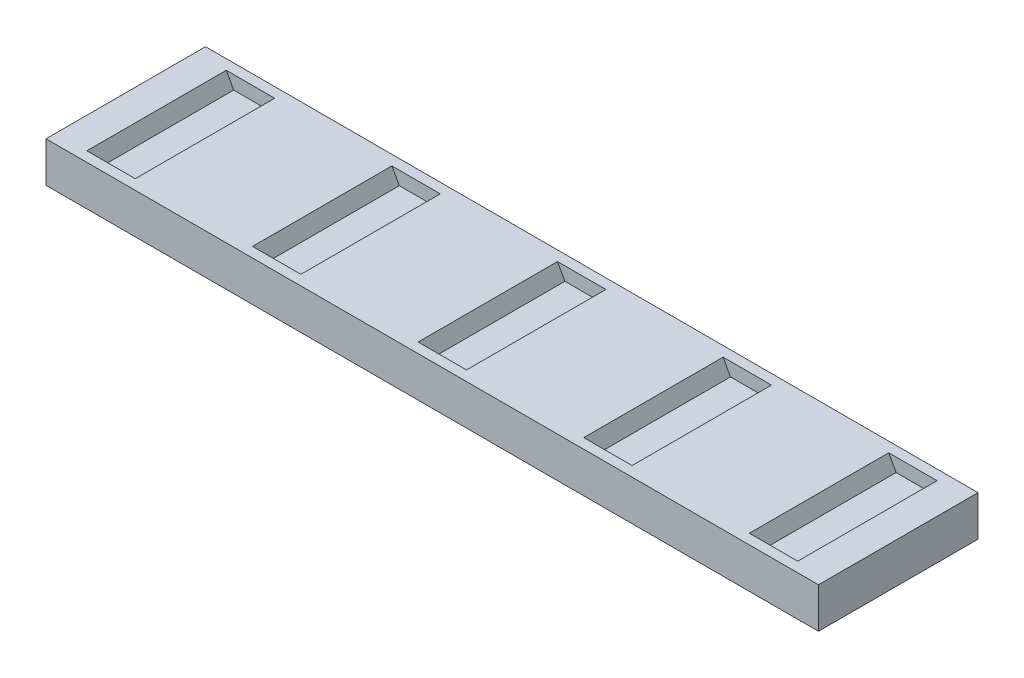
SolidWorks part; units mm, degrees
material "ABS"
ref_plane "Front Plane" through (0, 0, 0) normal (0, 0, 1) x (1, 0, 0)
ref_plane "Top Plane" through (0, 0, 0) normal (0, 1, 0) x (1, 0, 0)
ref_plane "Right Plane" through (0, 0, 0) normal (1, 0, 0) x (0, 0, -1)
sketch "ｽｹｯﾁ1" plane through (0, 0, 0) normal (0, 0, 1) x (1, 0, 0)
  line L0 (0, 0) -> (167.7493, 0) construction
  line B0 (0, 6.1517) -> (0, -7.9464) construction
  line B1 (-3.1032, 0) -> (3.1032, 0)
  line B2 (3.1032, 0) -> (2.3481, -2.0746)
  line B3 (1.0607, -2.976) -> (-1.0607, -2.976)
  line B4 (-2.3481, -2.0746) -> (-3.1032, 0)
  arc B5 (2.3481, -2.0746) -> (1.0607, -2.976) centre (1.0607, -1.606) cw
  arc B6 (-1.0607, -2.976) -> (-2.3481, -2.0746) centre (-1.0607, -1.606) cw
sketch_block_instance "ﾌﾞﾛｯｸ1-1"
sketch_block "ﾌﾞﾛｯｸ1" parameters "D2"=1.37, "D1"=40
sketch "ｽｹｯﾁ3" plane through (0, 0, 0) normal (0, 0, 1) x (1, 0, 0)
  line L0 (0, 6.1517) -> (0, -7.9464) construction
  line L1 (-2.3481, -2.0746) -> (-3.1032, 0) construction
  line L2 (1.0607, -2.976) -> (-1.0607, -2.976) construction
  line L3 (3.1032, 0) -> (2.3481, -2.0746) construction
  line L4 (3.1032, 0) -> (9.5968, 0)
  line L5 (0, 0) -> (167.7493, 0) construction
  line L6 (10.3519, -2.0746) -> (9.5968, 0)
  line L7 (13.7607, -2.976) -> (11.6393, -2.976)
  line L8 (0, 6.1517) -> (0, -7.9464) construction
  line L9 (-2.3481, -2.0746) -> (-3.1032, 0)
  line L10 (1.0607, -2.976) -> (-1.0607, -2.976)
  line L11 (3.1032, 0) -> (2.3481, -2.0746)
  line L12 (15.8032, 0) -> (15.0481, -2.0746)
  line L13 (12.7, 6.1517) -> (12.7, -7.9464) construction
  line L14 (15.8032, 0) -> (22.2968, 0)
  line L15 (23.0519, -2.0746) -> (22.2968, 0)
  line L16 (26.4607, -2.976) -> (24.3393, -2.976)
  line L17 (28.5032, 0) -> (27.7481, -2.0746)
  line L18 (25.4, 6.1517) -> (25.4, -7.9464) construction
  line L19 (28.5032, 0) -> (34.9968, 0)
  line L20 (35.7519, -2.0746) -> (34.9968, 0)
  line L21 (39.1607, -2.976) -> (37.0393, -2.976)
  line L22 (41.2032, 0) -> (40.4481, -2.0746)
  line L23 (38.1, 6.1517) -> (38.1, -7.9464) construction
  line L24 (41.2032, 0) -> (47.6968, 0)
  line L25 (48.4519, -2.0746) -> (47.6968, 0)
  line L26 (51.8607, -2.976) -> (49.7393, -2.976)
  line L27 (53.9032, 0) -> (53.1481, -2.0746)
  line L28 (50.8, 6.1517) -> (50.8, -7.9464) construction
  line L29 (53.9032, 0) -> (60.3968, 0)
  line L30 (61.1519, -2.0746) -> (60.3968, 0)
  line L31 (64.5607, -2.976) -> (62.4393, -2.976)
  line L32 (66.6032, 0) -> (65.8481, -2.0746)
  line L33 (63.5, 6.1517) -> (63.5, -7.9464) construction
  line L34 (66.6032, 0) -> (73.0968, 0)
  line L35 (73.8519, -2.0746) -> (73.0968, 0)
  line L36 (77.2607, -2.976) -> (75.1393, -2.976)
  line L37 (79.3032, 0) -> (78.5481, -2.0746)
  line L38 (76.2, 6.1517) -> (76.2, -7.9464) construction
  line L39 (79.3032, 0) -> (85.7968, 0)
  line L40 (86.5519, -2.0746) -> (85.7968, 0)
  line L41 (89.9607, -2.976) -> (87.8393, -2.976)
  line L42 (92.0032, 0) -> (91.2481, -2.0746)
  line L43 (88.9, 6.1517) -> (88.9, -7.9464) construction
  line L44 (92.0032, 0) -> (98.4968, 0)
  line L45 (99.2519, -2.0746) -> (98.4968, 0)
  line L46 (102.6607, -2.976) -> (100.5393, -2.976)
  line L47 (104.7032, 0) -> (103.9481, -2.0746)
  line L48 (101.6, 6.1517) -> (101.6, -7.9464) construction
  line L49 (104.7032, 0) -> (111.1968, 0)
  line L50 (111.9519, -2.0746) -> (111.1968, 0)
  line L51 (115.3607, -2.976) -> (113.2393, -2.976)
  line L52 (117.4032, 0) -> (116.6481, -2.0746)
  line L53 (114.3, 6.1517) -> (114.3, -7.9464) construction
  line L54 (117.4032, 0) -> (123.8968, 0)
  line L55 (124.6519, -2.0746) -> (123.8968, 0)
  line L56 (128.0607, -2.976) -> (125.9393, -2.976)
  line L57 (130.1032, 0) -> (129.3481, -2.0746)
  line L58 (127, 6.1517) -> (127, -7.9464) construction
  line L59 (130.1032, 0) -> (136.5968, 0)
  line L60 (137.3519, -2.0746) -> (136.5968, 0)
  line L61 (140.7607, -2.976) -> (138.6393, -2.976)
  line L62 (142.8032, 0) -> (142.0481, -2.0746)
  line L63 (139.7, 6.1517) -> (139.7, -7.9464) construction
  line L64 (142.8032, 0) -> (149.2968, 0)
  line L65 (150.0519, -2.0746) -> (149.2968, 0)
  line L66 (153.4607, -2.976) -> (151.3393, -2.976)
  line L67 (155.5032, 0) -> (154.7481, -2.0746)
  line L68 (152.4, 6.1517) -> (152.4, -7.9464) construction
  line L69 (155.5032, 0) -> (161.9968, 0)
  line L70 (162.7519, -2.0746) -> (161.9968, 0)
  line L71 (166.1607, -2.976) -> (164.0393, -2.976)
  line L72 (168.2032, 0) -> (167.4481, -2.0746)
  line L73 (165.1, 6.1517) -> (165.1, -7.9464) construction
  line L74 (168.2032, 0) -> (174.6968, 0)
  line L75 (175.4519, -2.0746) -> (174.6968, 0)
  line L76 (178.8607, -2.976) -> (176.7393, -2.976)
  line L77 (180.9032, 0) -> (180.1481, -2.0746)
  line L78 (177.8, 6.1517) -> (177.8, -7.9464) construction
  line L79 (180.9032, 0) -> (187.3968, 0)
  line L80 (188.1519, -2.0746) -> (187.3968, 0)
  line L81 (191.5607, -2.976) -> (189.4393, -2.976)
  line L82 (193.6032, 0) -> (192.8481, -2.0746)
  line L83 (190.5, 6.1517) -> (190.5, -7.9464) construction
  line L84 (193.6032, 0) -> (200.0968, 0)
  line L85 (200.8519, -2.0746) -> (200.0968, 0)
  line L86 (204.2607, -2.976) -> (202.1393, -2.976)
  line L87 (206.3032, 0) -> (205.5481, -2.0746)
  line L88 (203.2, 6.1517) -> (203.2, -7.9464) construction
  line L89 (206.3032, 0) -> (212.7968, 0)
  line L90 (213.5519, -2.0746) -> (212.7968, 0)
  line L91 (216.9607, -2.976) -> (214.8393, -2.976)
  line L92 (219.0032, 0) -> (218.2481, -2.0746)
  line L93 (215.9, 6.1517) -> (215.9, -7.9464) construction
  line L94 (219.0032, 0) -> (225.4968, 0)
  line L95 (226.2519, -2.0746) -> (225.4968, 0)
  line L96 (229.6607, -2.976) -> (227.5393, -2.976)
  line L97 (231.7032, 0) -> (230.9481, -2.0746)
  line L98 (228.6, 6.1517) -> (228.6, -7.9464) construction
  line L99 (231.7032, 0) -> (238.1968, 0)
  arc A0 (-2.3481, -2.0746) -> (-1.0607, -2.976) centre (-1.0607, -1.606) ccw construction
  arc A1 (1.0607, -2.976) -> (2.3481, -2.0746) centre (1.0607, -1.606) ccw construction
  arc A2 (10.3519, -2.0746) -> (11.6393, -2.976) centre (11.6393, -1.606) ccw
  arc A3 (13.7607, -2.976) -> (15.0481, -2.0746) centre (13.7607, -1.606) ccw
  arc A4 (-2.3481, -2.0746) -> (-1.0607, -2.976) centre (-1.0607, -1.606) ccw
  arc A5 (1.0607, -2.976) -> (2.3481, -2.0746) centre (1.0607, -1.606) ccw
  arc A6 (23.0519, -2.0746) -> (24.3393, -2.976) centre (24.3393, -1.606) ccw
  arc A7 (26.4607, -2.976) -> (27.7481, -2.0746) centre (26.4607, -1.606) ccw
  arc A8 (35.7519, -2.0746) -> (37.0393, -2.976) centre (37.0393, -1.606) ccw
  arc A9 (39.1607, -2.976) -> (40.4481, -2.0746) centre (39.1607, -1.606) ccw
  arc A10 (48.4519, -2.0746) -> (49.7393, -2.976) centre (49.7393, -1.606) ccw
  arc A11 (51.8607, -2.976) -> (53.1481, -2.0746) centre (51.8607, -1.606) ccw
  arc A12 (61.1519, -2.0746) -> (62.4393, -2.976) centre (62.4393, -1.606) ccw
  arc A13 (64.5607, -2.976) -> (65.8481, -2.0746) centre (64.5607, -1.606) ccw
  arc A14 (73.8519, -2.0746) -> (75.1393, -2.976) centre (75.1393, -1.606) ccw
  arc A15 (77.2607, -2.976) -> (78.5481, -2.0746) centre (77.2607, -1.606) ccw
  arc A16 (86.5519, -2.0746) -> (87.8393, -2.976) centre (87.8393, -1.606) ccw
  arc A17 (89.9607, -2.976) -> (91.2481, -2.0746) centre (89.9607, -1.606) ccw
  arc A18 (99.2519, -2.0746) -> (100.5393, -2.976) centre (100.5393, -1.606) ccw
  arc A19 (102.6607, -2.976) -> (103.9481, -2.0746) centre (102.6607, -1.606) ccw
  arc A20 (111.9519, -2.0746) -> (113.2393, -2.976) centre (113.2393, -1.606) ccw
  arc A21 (115.3607, -2.976) -> (116.6481, -2.0746) centre (115.3607, -1.606) ccw
  arc A22 (124.6519, -2.0746) -> (125.9393, -2.976) centre (125.9393, -1.606) ccw
  arc A23 (128.0607, -2.976) -> (129.3481, -2.0746) centre (128.0607, -1.606) ccw
  arc A24 (137.3519, -2.0746) -> (138.6393, -2.976) centre (138.6393, -1.606) ccw
  arc A25 (140.7607, -2.976) -> (142.0481, -2.0746) centre (140.7607, -1.606) ccw
  arc A26 (150.0519, -2.0746) -> (151.3393, -2.976) centre (151.3393, -1.606) ccw
  arc A27 (153.4607, -2.976) -> (154.7481, -2.0746) centre (153.4607, -1.606) ccw
  arc A28 (162.7519, -2.0746) -> (164.0393, -2.976) centre (164.0393, -1.606) ccw
  arc A29 (166.1607, -2.976) -> (167.4481, -2.0746) centre (166.1607, -1.606) ccw
  arc A30 (175.4519, -2.0746) -> (176.7393, -2.976) centre (176.7393, -1.606) ccw
  arc A31 (178.8607, -2.976) -> (180.1481, -2.0746) centre (178.8607, -1.606) ccw
  arc A32 (188.1519, -2.0746) -> (189.4393, -2.976) centre (189.4393, -1.606) ccw
  arc A33 (191.5607, -2.976) -> (192.8481, -2.0746) centre (191.5607, -1.606) ccw
  arc A34 (200.8519, -2.0746) -> (202.1393, -2.976) centre (202.1393, -1.606) ccw
  arc A35 (204.2607, -2.976) -> (205.5481, -2.0746) centre (204.2607, -1.606) ccw
  arc A36 (213.5519, -2.0746) -> (214.8393, -2.976) centre (214.8393, -1.606) ccw
  arc A37 (216.9607, -2.976) -> (218.2481, -2.0746) centre (216.9607, -1.606) ccw
  arc A38 (226.2519, -2.0746) -> (227.5393, -2.976) centre (227.5393, -1.606) ccw
  arc A39 (229.6607, -2.976) -> (230.9481, -2.0746) centre (229.6607, -1.606) ccw
  dimension "D1" = 19
  dimension "D2" = 12.7
sketch "ｽｹｯﾁ4" plane through (0, 0, 0) normal (0, 0, 1) x (1, 0, 0)
  line L0 (0, 6.1517) -> (0, -7.9464) construction
  line L1 (1.0607, -2.976) -> (-1.0607, -2.976) construction
  line L2 (3.1032, 0) -> (2.3481, -2.0746) construction
  line L3 (3.1032, 0) -> (9.5968, 0) construction
  line L4 (10.3519, -2.0746) -> (9.5968, 0) construction
  line L5 (13.7607, -2.976) -> (11.6393, -2.976) construction
  line L6 (15.8032, 0) -> (15.0481, -2.0746) construction
  line L7 (15.8032, 0) -> (22.2968, 0) construction
  line L8 (23.0519, -2.0746) -> (22.2968, 0) construction
  line L9 (26.4607, -2.976) -> (24.3393, -2.976) construction
  line L10 (28.5032, 0) -> (27.7481, -2.0746) construction
  line L11 (28.5032, 0) -> (34.9968, 0) construction
  line L12 (35.7519, -2.0746) -> (34.9968, 0) construction
  line L13 (39.1607, -2.976) -> (37.0393, -2.976) construction
  line L14 (41.2032, 0) -> (40.4481, -2.0746) construction
  line L15 (41.2032, 0) -> (47.6968, 0) construction
  line L16 (48.4519, -2.0746) -> (47.6968, 0) construction
  line L17 (51.8607, -2.976) -> (49.7393, -2.976) construction
  line L18 (53.9032, 0) -> (53.1481, -2.0746) construction
  line L19 (53.9032, 0) -> (60.3968, 0) construction
  line L20 (61.1519, -2.0746) -> (60.3968, 0) construction
  line L21 (64.5607, -2.976) -> (62.4393, -2.976) construction
  line L22 (66.6032, 0) -> (65.8481, -2.0746) construction
  line L23 (66.6032, 0) -> (73.0968, 0) construction
  line L24 (73.8519, -2.0746) -> (73.0968, 0) construction
  line L25 (77.2607, -2.976) -> (75.1393, -2.976) construction
  line L26 (79.3032, 0) -> (78.5481, -2.0746) construction
  line L27 (79.3032, 0) -> (85.7968, 0) construction
  line L28 (86.5519, -2.0746) -> (85.7968, 0) construction
  line L29 (89.9607, -2.976) -> (87.8393, -2.976) construction
  line L30 (92.0032, 0) -> (91.2481, -2.0746) construction
  line L31 (92.0032, 0) -> (98.4968, 0) construction
  line L32 (99.2519, -2.0746) -> (98.4968, 0) construction
  line L33 (102.6607, -2.976) -> (100.5393, -2.976) construction
  line L34 (104.7032, 0) -> (103.9481, -2.0746) construction
  line L35 (104.7032, 0) -> (111.1968, 0) construction
  line L36 (111.9519, -2.0746) -> (111.1968, 0) construction
  line L37 (115.3607, -2.976) -> (113.2393, -2.976) construction
  line L38 (117.4032, 0) -> (116.6481, -2.0746) construction
  line L39 (117.4032, 0) -> (123.8968, 0) construction
  line L40 (124.6519, -2.0746) -> (123.8968, 0) construction
  line L41 (128.0607, -2.976) -> (125.9393, -2.976) construction
  line L42 (130.1032, 0) -> (129.3481, -2.0746) construction
  line L43 (130.1032, 0) -> (136.5968, 0) construction
  line L44 (137.3519, -2.0746) -> (136.5968, 0) construction
  line L45 (140.7607, -2.976) -> (138.6393, -2.976) construction
  line L46 (142.8032, 0) -> (142.0481, -2.0746) construction
  line L47 (142.8032, 0) -> (149.2968, 0) construction
  line L48 (150.0519, -2.0746) -> (149.2968, 0) construction
  line L49 (153.4607, -2.976) -> (151.3393, -2.976) construction
  line L50 (155.5032, 0) -> (154.7481, -2.0746) construction
  line L51 (155.5032, 0) -> (161.9968, 0) construction
  line L52 (162.7519, -2.0746) -> (161.9968, 0) construction
  line L53 (166.1607, -2.976) -> (164.0393, -2.976) construction
  line L54 (168.2032, 0) -> (167.4481, -2.0746) construction
  line L55 (168.2032, 0) -> (174.6968, 0) construction
  line L56 (175.4519, -2.0746) -> (174.6968, 0) construction
  line L57 (178.8607, -2.976) -> (176.7393, -2.976) construction
  line L58 (180.9032, 0) -> (180.1481, -2.0746) construction
  line L59 (180.9032, 0) -> (187.3968, 0) construction
  line L60 (188.1519, -2.0746) -> (187.3968, 0) construction
  line L61 (191.5607, -2.976) -> (189.4393, -2.976) construction
  line L62 (193.6032, 0) -> (192.8481, -2.0746) construction
  line L63 (193.6032, 0) -> (200.0968, 0) construction
  line L64 (200.8519, -2.0746) -> (200.0968, 0) construction
  line L65 (204.2607, -2.976) -> (202.1393, -2.976) construction
  line L66 (206.3032, 0) -> (205.5481, -2.0746) construction
  line L67 (206.3032, 0) -> (212.7968, 0) construction
  line L68 (213.5519, -2.0746) -> (212.7968, 0) construction
  line L69 (216.9607, -2.976) -> (214.8393, -2.976) construction
  line L70 (219.0032, 0) -> (218.2481, -2.0746) construction
  line L71 (219.0032, 0) -> (225.4968, 0) construction
  line L72 (226.2519, -2.0746) -> (225.4968, 0) construction
  line L73 (229.6607, -2.976) -> (227.5393, -2.976) construction
  line L74 (115, 61.4098) -> (115, -57.3786) construction
  line L77 (1.0607, -2.976) -> (0, -2.976)
  line L78 (3.1032, 0) -> (2.3481, -2.0746)
  line L79 (3.1032, 0) -> (9.5968, 0)
  line L80 (10.3519, -2.0746) -> (9.5968, 0)
  line L81 (13.7607, -2.976) -> (11.6393, -2.976)
  line L82 (15.8032, 0) -> (15.0481, -2.0746)
  line L83 (15.8032, 0) -> (22.2968, 0)
  line L84 (23.0519, -2.0746) -> (22.2968, 0)
  line L85 (26.4607, -2.976) -> (24.3393, -2.976)
  line L86 (28.5032, 0) -> (27.7481, -2.0746)
  line L87 (28.5032, 0) -> (34.9968, 0)
  line L88 (35.7519, -2.0746) -> (34.9968, 0)
  line L89 (39.1607, -2.976) -> (37.0393, -2.976)
  line L90 (41.2032, 0) -> (40.4481, -2.0746)
  line L91 (41.2032, 0) -> (47.6968, 0)
  line L92 (48.4519, -2.0746) -> (47.6968, 0)
  line L93 (51.8607, -2.976) -> (49.7393, -2.976)
  line L94 (53.9032, 0) -> (53.1481, -2.0746)
  line L95 (53.9032, 0) -> (60.3968, 0)
  line L96 (61.1519, -2.0746) -> (60.3968, 0)
  line L97 (64.5607, -2.976) -> (62.4393, -2.976)
  line L98 (66.6032, 0) -> (65.8481, -2.0746)
  line L99 (66.6032, 0) -> (73.0968, 0)
  line L100 (73.8519, -2.0746) -> (73.0968, 0)
  line L101 (77.2607, -2.976) -> (75.1393, -2.976)
  line L102 (79.3032, 0) -> (78.5481, -2.0746)
  line L103 (79.3032, 0) -> (85.7968, 0)
  line L104 (86.5519, -2.0746) -> (85.7968, 0)
  line L105 (89.9607, -2.976) -> (87.8393, -2.976)
  line L106 (92.0032, 0) -> (91.2481, -2.0746)
  line L107 (92.0032, 0) -> (98.4968, 0)
  line L108 (99.2519, -2.0746) -> (98.4968, 0)
  line L109 (102.6607, -2.976) -> (100.5393, -2.976)
  line L110 (104.7032, 0) -> (103.9481, -2.0746)
  line L111 (104.7032, 0) -> (111.1968, 0)
  line L112 (111.9519, -2.0746) -> (111.1968, 0)
  line L113 (115.3607, -2.976) -> (113.2393, -2.976)
  line L114 (117.4032, 0) -> (116.6481, -2.0746)
  line L115 (117.4032, 0) -> (123.8968, 0)
  line L116 (124.6519, -2.0746) -> (123.8968, 0)
  line L117 (128.0607, -2.976) -> (125.9393, -2.976)
  line L118 (130.1032, 0) -> (129.3481, -2.0746)
  line L119 (130.1032, 0) -> (136.5968, 0)
  line L120 (137.3519, -2.0746) -> (136.5968, 0)
  line L121 (140.7607, -2.976) -> (138.6393, -2.976)
  line L122 (142.8032, 0) -> (142.0481, -2.0746)
  line L123 (142.8032, 0) -> (149.2968, 0)
  line L124 (150.0519, -2.0746) -> (149.2968, 0)
  line L125 (153.4607, -2.976) -> (151.3393, -2.976)
  line L126 (155.5032, 0) -> (154.7481, -2.0746)
  line L127 (155.5032, 0) -> (161.9968, 0)
  line L128 (162.7519, -2.0746) -> (161.9968, 0)
  line L129 (166.1607, -2.976) -> (164.0393, -2.976)
  line L130 (168.2032, 0) -> (167.4481, -2.0746)
  line L131 (168.2032, 0) -> (174.6968, 0)
  line L132 (175.4519, -2.0746) -> (174.6968, 0)
  line L133 (178.8607, -2.976) -> (176.7393, -2.976)
  line L134 (180.9032, 0) -> (180.1481, -2.0746)
  line L135 (180.9032, 0) -> (187.3968, 0)
  line L136 (188.1519, -2.0746) -> (187.3968, 0)
  line L137 (191.5607, -2.976) -> (189.4393, -2.976)
  line L138 (193.6032, 0) -> (192.8481, -2.0746)
  line L139 (193.6032, 0) -> (200.0968, 0)
  line L140 (200.8519, -2.0746) -> (200.0968, 0)
  line L141 (204.2607, -2.976) -> (202.1393, -2.976)
  line L142 (206.3032, 0) -> (205.5481, -2.0746)
  line L143 (206.3032, 0) -> (212.7968, 0)
  line L144 (213.5519, -2.0746) -> (212.7968, 0)
  line L145 (216.9607, -2.976) -> (214.8393, -2.976)
  line L146 (219.0032, 0) -> (218.2481, -2.0746)
  line L147 (219.0032, 0) -> (225.4968, 0)
  line L148 (226.2519, -2.0746) -> (225.4968, 0)
  line L149 (230, -2.976) -> (227.5393, -2.976)
  line L150 (0, -7) -> (55.8373, -7) construction
  line L152 (0, -2.976) -> (0, -15)
  line L153 (0, -15) -> (230, -15)
  line L154 (230, -2.976) -> (230, -15)
  arc A1 (1.0607, -2.976) -> (2.3481, -2.0746) centre (1.0607, -1.606) ccw construction
  arc A2 (10.3519, -2.0746) -> (11.6393, -2.976) centre (11.6393, -1.606) ccw construction
  arc A3 (13.7607, -2.976) -> (15.0481, -2.0746) centre (13.7607, -1.606) ccw construction
  arc A4 (23.0519, -2.0746) -> (24.3393, -2.976) centre (24.3393, -1.606) ccw construction
  arc A5 (26.4607, -2.976) -> (27.7481, -2.0746) centre (26.4607, -1.606) ccw construction
  arc A6 (35.7519, -2.0746) -> (37.0393, -2.976) centre (37.0393, -1.606) ccw construction
  arc A7 (39.1607, -2.976) -> (40.4481, -2.0746) centre (39.1607, -1.606) ccw construction
  arc A8 (48.4519, -2.0746) -> (49.7393, -2.976) centre (49.7393, -1.606) ccw construction
  arc A9 (51.8607, -2.976) -> (53.1481, -2.0746) centre (51.8607, -1.606) ccw construction
  arc A10 (61.1519, -2.0746) -> (62.4393, -2.976) centre (62.4393, -1.606) ccw construction
  arc A11 (64.5607, -2.976) -> (65.8481, -2.0746) centre (64.5607, -1.606) ccw construction
  arc A12 (73.8519, -2.0746) -> (75.1393, -2.976) centre (75.1393, -1.606) ccw construction
  arc A13 (77.2607, -2.976) -> (78.5481, -2.0746) centre (77.2607, -1.606) ccw construction
  arc A14 (86.5519, -2.0746) -> (87.8393, -2.976) centre (87.8393, -1.606) ccw construction
  arc A15 (89.9607, -2.976) -> (91.2481, -2.0746) centre (89.9607, -1.606) ccw construction
  arc A16 (99.2519, -2.0746) -> (100.5393, -2.976) centre (100.5393, -1.606) ccw construction
  arc A17 (102.6607, -2.976) -> (103.9481, -2.0746) centre (102.6607, -1.606) ccw construction
  arc A18 (111.9519, -2.0746) -> (113.2393, -2.976) centre (113.2393, -1.606) ccw construction
  arc A19 (115.3607, -2.976) -> (116.6481, -2.0746) centre (115.3607, -1.606) ccw construction
  arc A20 (124.6519, -2.0746) -> (125.9393, -2.976) centre (125.9393, -1.606) ccw construction
  arc A21 (128.0607, -2.976) -> (129.3481, -2.0746) centre (128.0607, -1.606) ccw construction
  arc A22 (137.3519, -2.0746) -> (138.6393, -2.976) centre (138.6393, -1.606) ccw construction
  arc A23 (140.7607, -2.976) -> (142.0481, -2.0746) centre (140.7607, -1.606) ccw construction
  arc A24 (150.0519, -2.0746) -> (151.3393, -2.976) centre (151.3393, -1.606) ccw construction
  arc A25 (153.4607, -2.976) -> (154.7481, -2.0746) centre (153.4607, -1.606) ccw construction
  arc A26 (162.7519, -2.0746) -> (164.0393, -2.976) centre (164.0393, -1.606) ccw construction
  arc A27 (166.1607, -2.976) -> (167.4481, -2.0746) centre (166.1607, -1.606) ccw construction
  arc A28 (175.4519, -2.0746) -> (176.7393, -2.976) centre (176.7393, -1.606) ccw construction
  arc A29 (178.8607, -2.976) -> (180.1481, -2.0746) centre (178.8607, -1.606) ccw construction
  arc A30 (188.1519, -2.0746) -> (189.4393, -2.976) centre (189.4393, -1.606) ccw construction
  arc A31 (191.5607, -2.976) -> (192.8481, -2.0746) centre (191.5607, -1.606) ccw construction
  arc A32 (200.8519, -2.0746) -> (202.1393, -2.976) centre (202.1393, -1.606) ccw construction
  arc A33 (204.2607, -2.976) -> (205.5481, -2.0746) centre (204.2607, -1.606) ccw construction
  arc A34 (213.5519, -2.0746) -> (214.8393, -2.976) centre (214.8393, -1.606) ccw construction
  arc A35 (216.9607, -2.976) -> (218.2481, -2.0746) centre (216.9607, -1.606) ccw construction
  arc A36 (226.2519, -2.0746) -> (227.5393, -2.976) centre (227.5393, -1.606) ccw construction
  arc A39 (1.0607, -2.976) -> (2.3481, -2.0746) centre (1.0607, -1.606) ccw
  arc A40 (10.3519, -2.0746) -> (11.6393, -2.976) centre (11.6393, -1.606) ccw
  arc A41 (13.7607, -2.976) -> (15.0481, -2.0746) centre (13.7607, -1.606) ccw
  arc A42 (23.0519, -2.0746) -> (24.3393, -2.976) centre (24.3393, -1.606) ccw
  arc A43 (26.4607, -2.976) -> (27.7481, -2.0746) centre (26.4607, -1.606) ccw
  arc A44 (35.7519, -2.0746) -> (37.0393, -2.976) centre (37.0393, -1.606) ccw
  arc A45 (39.1607, -2.976) -> (40.4481, -2.0746) centre (39.1607, -1.606) ccw
  arc A46 (48.4519, -2.0746) -> (49.7393, -2.976) centre (49.7393, -1.606) ccw
  arc A47 (51.8607, -2.976) -> (53.1481, -2.0746) centre (51.8607, -1.606) ccw
  arc A48 (61.1519, -2.0746) -> (62.4393, -2.976) centre (62.4393, -1.606) ccw
  arc A49 (64.5607, -2.976) -> (65.8481, -2.0746) centre (64.5607, -1.606) ccw
  arc A50 (73.8519, -2.0746) -> (75.1393, -2.976) centre (75.1393, -1.606) ccw
  arc A51 (77.2607, -2.976) -> (78.5481, -2.0746) centre (77.2607, -1.606) ccw
  arc A52 (86.5519, -2.0746) -> (87.8393, -2.976) centre (87.8393, -1.606) ccw
  arc A53 (89.9607, -2.976) -> (91.2481, -2.0746) centre (89.9607, -1.606) ccw
  arc A54 (99.2519, -2.0746) -> (100.5393, -2.976) centre (100.5393, -1.606) ccw
  arc A55 (102.6607, -2.976) -> (103.9481, -2.0746) centre (102.6607, -1.606) ccw
  arc A56 (111.9519, -2.0746) -> (113.2393, -2.976) centre (113.2393, -1.606) ccw
  arc A57 (115.3607, -2.976) -> (116.6481, -2.0746) centre (115.3607, -1.606) ccw
  arc A58 (124.6519, -2.0746) -> (125.9393, -2.976) centre (125.9393, -1.606) ccw
  arc A59 (128.0607, -2.976) -> (129.3481, -2.0746) centre (128.0607, -1.606) ccw
  arc A60 (137.3519, -2.0746) -> (138.6393, -2.976) centre (138.6393, -1.606) ccw
  arc A61 (140.7607, -2.976) -> (142.0481, -2.0746) centre (140.7607, -1.606) ccw
  arc A62 (150.0519, -2.0746) -> (151.3393, -2.976) centre (151.3393, -1.606) ccw
  arc A63 (153.4607, -2.976) -> (154.7481, -2.0746) centre (153.4607, -1.606) ccw
  arc A64 (162.7519, -2.0746) -> (164.0393, -2.976) centre (164.0393, -1.606) ccw
  arc A65 (166.1607, -2.976) -> (167.4481, -2.0746) centre (166.1607, -1.606) ccw
  arc A66 (175.4519, -2.0746) -> (176.7393, -2.976) centre (176.7393, -1.606) ccw
  arc A67 (178.8607, -2.976) -> (180.1481, -2.0746) centre (178.8607, -1.606) ccw
  arc A68 (188.1519, -2.0746) -> (189.4393, -2.976) centre (189.4393, -1.606) ccw
  arc A69 (191.5607, -2.976) -> (192.8481, -2.0746) centre (191.5607, -1.606) ccw
  arc A70 (200.8519, -2.0746) -> (202.1393, -2.976) centre (202.1393, -1.606) ccw
  arc A71 (204.2607, -2.976) -> (205.5481, -2.0746) centre (204.2607, -1.606) ccw
  arc A72 (213.5519, -2.0746) -> (214.8393, -2.976) centre (214.8393, -1.606) ccw
  arc A73 (216.9607, -2.976) -> (218.2481, -2.0746) centre (216.9607, -1.606) ccw
  arc A74 (226.2519, -2.0746) -> (227.5393, -2.976) centre (227.5393, -1.606) ccw
  point P11 (25, -7)
  point P17 (85, -7)
  point P29 (145, -7)
  point P31 (205, -7)
  dimension "D1" = 15
  dimension "D2" = 7
  dimension "D3" = 25
  dimension "D4" = 85
  dimension "D5" = 230
ref_plane "平面1" through (0, 0, -1.55) normal (0, 0, 1) x (1, 0, 0)
sketch "ｽｹｯﾁ5" plane through (0, 0, -1.55) normal (0, 0, 1) x (1, 0, 0)
  line L76 (230, -2.976) -> (227.5393, -2.976)
  line L77 (230, -15) -> (230, -2.976)
  line L78 (0, -15) -> (230, -15)
  line L79 (0, -2.976) -> (0, -15)
  line L80 (1.0607, -2.976) -> (0, -2.976)
  line L81 (3.1032, 0) -> (2.3481, -2.0746)
  line L82 (9.5968, 0) -> (3.1032, 0)
  line L83 (10.3519, -2.0746) -> (9.5968, 0)
  line L84 (13.7607, -2.976) -> (11.6393, -2.976)
  line L85 (15.8032, 0) -> (15.0481, -2.0746)
  line L86 (22.2968, 0) -> (15.8032, 0)
  line L87 (23.0519, -2.0746) -> (22.2968, 0)
  line L88 (26.4607, -2.976) -> (24.3393, -2.976)
  line L89 (28.5032, 0) -> (27.7481, -2.0746)
  line L90 (34.9968, 0) -> (28.5032, 0)
  line L91 (35.7519, -2.0746) -> (34.9968, 0)
  line L92 (39.1607, -2.976) -> (37.0393, -2.976)
  line L93 (41.2032, 0) -> (40.4481, -2.0746)
  line L94 (47.6968, 0) -> (41.2032, 0)
  line L95 (48.4519, -2.0746) -> (47.6968, 0)
  line L96 (51.8607, -2.976) -> (49.7393, -2.976)
  line L97 (53.9032, 0) -> (53.1481, -2.0746)
  line L98 (60.3968, 0) -> (53.9032, 0)
  line L99 (61.1519, -2.0746) -> (60.3968, 0)
  line L100 (64.5607, -2.976) -> (62.4393, -2.976)
  line L101 (66.6032, 0) -> (65.8481, -2.0746)
  line L102 (73.0968, 0) -> (66.6032, 0)
  line L103 (73.8519, -2.0746) -> (73.0968, 0)
  line L104 (77.2607, -2.976) -> (75.1393, -2.976)
  line L105 (79.3032, 0) -> (78.5481, -2.0746)
  line L106 (85.7968, 0) -> (79.3032, 0)
  line L107 (86.5519, -2.0746) -> (85.7968, 0)
  line L108 (89.9607, -2.976) -> (87.8393, -2.976)
  line L109 (92.0032, 0) -> (91.2481, -2.0746)
  line L110 (98.4968, 0) -> (92.0032, 0)
  line L111 (99.2519, -2.0746) -> (98.4968, 0)
  line L112 (102.6607, -2.976) -> (100.5393, -2.976)
  line L113 (104.7032, 0) -> (103.9481, -2.0746)
  line L114 (111.1968, 0) -> (104.7032, 0)
  line L115 (111.9519, -2.0746) -> (111.1968, 0)
  line L116 (115.3607, -2.976) -> (113.2393, -2.976)
  line L117 (117.4032, 0) -> (116.6481, -2.0746)
  line L118 (123.8968, 0) -> (117.4032, 0)
  line L119 (124.6519, -2.0746) -> (123.8968, 0)
  line L120 (128.0607, -2.976) -> (125.9393, -2.976)
  line L121 (130.1032, 0) -> (129.3481, -2.0746)
  line L122 (136.5968, 0) -> (130.1032, 0)
  line L123 (137.3519, -2.0746) -> (136.5968, 0)
  line L124 (140.7607, -2.976) -> (138.6393, -2.976)
  line L125 (142.8032, 0) -> (142.0481, -2.0746)
  line L126 (149.2968, 0) -> (142.8032, 0)
  line L127 (150.0519, -2.0746) -> (149.2968, 0)
  line L128 (153.4607, -2.976) -> (151.3393, -2.976)
  line L129 (155.5032, 0) -> (154.7481, -2.0746)
  line L130 (161.9968, 0) -> (155.5032, 0)
  line L131 (162.7519, -2.0746) -> (161.9968, 0)
  line L132 (166.1607, -2.976) -> (164.0393, -2.976)
  line L133 (168.2032, 0) -> (167.4481, -2.0746)
  line L134 (174.6968, 0) -> (168.2032, 0)
  line L135 (175.4519, -2.0746) -> (174.6968, 0)
  line L136 (178.8607, -2.976) -> (176.7393, -2.976)
  line L137 (180.9032, 0) -> (180.1481, -2.0746)
  line L138 (187.3968, 0) -> (180.9032, 0)
  line L139 (188.1519, -2.0746) -> (187.3968, 0)
  line L140 (191.5607, -2.976) -> (189.4393, -2.976)
  line L141 (193.6032, 0) -> (192.8481, -2.0746)
  line L142 (200.0968, 0) -> (193.6032, 0)
  line L143 (200.8519, -2.0746) -> (200.0968, 0)
  line L144 (204.2607, -2.976) -> (202.1393, -2.976)
  line L145 (206.3032, 0) -> (205.5481, -2.0746)
  line L146 (212.7968, 0) -> (206.3032, 0)
  line L147 (213.5519, -2.0746) -> (212.7968, 0)
  line L148 (216.9607, -2.976) -> (214.8393, -2.976)
  line L149 (219.0032, 0) -> (218.2481, -2.0746)
  line L150 (225.4968, 0) -> (219.0032, 0)
  line L151 (226.2519, -2.0746) -> (225.4968, 0)
  line L152 (230, -2.976) -> (227.5393, -2.976)
  line L153 (230, -15) -> (230, -2.976)
  line L154 (0, -15) -> (230, -15)
  line L155 (0, -2.976) -> (0, -15)
  line L156 (1.0607, -2.976) -> (0, -2.976)
  line L157 (3.1032, 0) -> (2.3481, -2.0746)
  line L158 (9.5968, 0) -> (3.1032, 0)
  line L159 (10.3519, -2.0746) -> (9.5968, 0)
  line L160 (13.7607, -2.976) -> (11.6393, -2.976)
  line L161 (15.8032, 0) -> (15.0481, -2.0746)
  line L162 (22.2968, 0) -> (15.8032, 0)
  line L163 (23.0519, -2.0746) -> (22.2968, 0)
  line L164 (26.4607, -2.976) -> (24.3393, -2.976)
  line L165 (28.5032, 0) -> (27.7481, -2.0746)
  line L166 (34.9968, 0) -> (28.5032, 0)
  line L167 (35.7519, -2.0746) -> (34.9968, 0)
  line L168 (39.1607, -2.976) -> (37.0393, -2.976)
  line L169 (41.2032, 0) -> (40.4481, -2.0746)
  line L170 (47.6968, 0) -> (41.2032, 0)
  line L171 (48.4519, -2.0746) -> (47.6968, 0)
  line L172 (51.8607, -2.976) -> (49.7393, -2.976)
  line L173 (53.9032, 0) -> (53.1481, -2.0746)
  line L174 (60.3968, 0) -> (53.9032, 0)
  line L175 (61.1519, -2.0746) -> (60.3968, 0)
  line L176 (64.5607, -2.976) -> (62.4393, -2.976)
  line L177 (66.6032, 0) -> (65.8481, -2.0746)
  line L178 (73.0968, 0) -> (66.6032, 0)
  line L179 (73.8519, -2.0746) -> (73.0968, 0)
  line L180 (77.2607, -2.976) -> (75.1393, -2.976)
  line L181 (79.3032, 0) -> (78.5481, -2.0746)
  line L182 (85.7968, 0) -> (79.3032, 0)
  line L183 (86.5519, -2.0746) -> (85.7968, 0)
  line L184 (89.9607, -2.976) -> (87.8393, -2.976)
  line L185 (92.0032, 0) -> (91.2481, -2.0746)
  line L186 (98.4968, 0) -> (92.0032, 0)
  line L187 (99.2519, -2.0746) -> (98.4968, 0)
  line L188 (102.6607, -2.976) -> (100.5393, -2.976)
  line L189 (104.7032, 0) -> (103.9481, -2.0746)
  line L190 (111.1968, 0) -> (104.7032, 0)
  line L191 (111.9519, -2.0746) -> (111.1968, 0)
  line L192 (115.3607, -2.976) -> (113.2393, -2.976)
  line L193 (117.4032, 0) -> (116.6481, -2.0746)
  line L194 (123.8968, 0) -> (117.4032, 0)
  line L195 (124.6519, -2.0746) -> (123.8968, 0)
  line L196 (128.0607, -2.976) -> (125.9393, -2.976)
  line L197 (130.1032, 0) -> (129.3481, -2.0746)
  line L198 (136.5968, 0) -> (130.1032, 0)
  line L199 (137.3519, -2.0746) -> (136.5968, 0)
  line L200 (140.7607, -2.976) -> (138.6393, -2.976)
  line L201 (142.8032, 0) -> (142.0481, -2.0746)
  line L202 (149.2968, 0) -> (142.8032, 0)
  line L203 (150.0519, -2.0746) -> (149.2968, 0)
  line L204 (153.4607, -2.976) -> (151.3393, -2.976)
  line L205 (155.5032, 0) -> (154.7481, -2.0746)
  line L206 (161.9968, 0) -> (155.5032, 0)
  line L207 (162.7519, -2.0746) -> (161.9968, 0)
  line L208 (166.1607, -2.976) -> (164.0393, -2.976)
  line L209 (168.2032, 0) -> (167.4481, -2.0746)
  line L210 (174.6968, 0) -> (168.2032, 0)
  line L211 (175.4519, -2.0746) -> (174.6968, 0)
  line L212 (178.8607, -2.976) -> (176.7393, -2.976)
  line L213 (180.9032, 0) -> (180.1481, -2.0746)
  line L214 (187.3968, 0) -> (180.9032, 0)
  line L215 (188.1519, -2.0746) -> (187.3968, 0)
  line L216 (191.5607, -2.976) -> (189.4393, -2.976)
  line L217 (193.6032, 0) -> (192.8481, -2.0746)
  line L218 (200.0968, 0) -> (193.6032, 0)
  line L219 (200.8519, -2.0746) -> (200.0968, 0)
  line L220 (204.2607, -2.976) -> (202.1393, -2.976)
  line L221 (206.3032, 0) -> (205.5481, -2.0746)
  line L222 (212.7968, 0) -> (206.3032, 0)
  line L223 (213.5519, -2.0746) -> (212.7968, 0)
  line L224 (216.9607, -2.976) -> (214.8393, -2.976)
  line L225 (219.0032, 0) -> (218.2481, -2.0746)
  line L226 (225.4968, 0) -> (219.0032, 0)
  line L227 (226.2519, -2.0746) -> (225.4968, 0)
  arc A36 (1.0607, -2.976) -> (2.3481, -2.0746) centre (1.0607, -1.606) ccw
  arc A37 (10.3519, -2.0746) -> (11.6393, -2.976) centre (11.6393, -1.606) ccw
  arc A38 (13.7607, -2.976) -> (15.0481, -2.0746) centre (13.7607, -1.606) ccw
  arc A39 (23.0519, -2.0746) -> (24.3393, -2.976) centre (24.3393, -1.606) ccw
  arc A40 (26.4607, -2.976) -> (27.7481, -2.0746) centre (26.4607, -1.606) ccw
  arc A41 (35.7519, -2.0746) -> (37.0393, -2.976) centre (37.0393, -1.606) ccw
  arc A42 (39.1607, -2.976) -> (40.4481, -2.0746) centre (39.1607, -1.606) ccw
  arc A43 (48.4519, -2.0746) -> (49.7393, -2.976) centre (49.7393, -1.606) ccw
  arc A44 (51.8607, -2.976) -> (53.1481, -2.0746) centre (51.8607, -1.606) ccw
  arc A45 (61.1519, -2.0746) -> (62.4393, -2.976) centre (62.4393, -1.606) ccw
  arc A46 (64.5607, -2.976) -> (65.8481, -2.0746) centre (64.5607, -1.606) ccw
  arc A47 (73.8519, -2.0746) -> (75.1393, -2.976) centre (75.1393, -1.606) ccw
  arc A48 (77.2607, -2.976) -> (78.5481, -2.0746) centre (77.2607, -1.606) ccw
  arc A49 (86.5519, -2.0746) -> (87.8393, -2.976) centre (87.8393, -1.606) ccw
  arc A50 (89.9607, -2.976) -> (91.2481, -2.0746) centre (89.9607, -1.606) ccw
  arc A51 (99.2519, -2.0746) -> (100.5393, -2.976) centre (100.5393, -1.606) ccw
  arc A52 (102.6607, -2.976) -> (103.9481, -2.0746) centre (102.6607, -1.606) ccw
  arc A53 (111.9519, -2.0746) -> (113.2393, -2.976) centre (113.2393, -1.606) ccw
  arc A54 (115.3607, -2.976) -> (116.6481, -2.0746) centre (115.3607, -1.606) ccw
  arc A55 (124.6519, -2.0746) -> (125.9393, -2.976) centre (125.9393, -1.606) ccw
  arc A56 (128.0607, -2.976) -> (129.3481, -2.0746) centre (128.0607, -1.606) ccw
  arc A57 (137.3519, -2.0746) -> (138.6393, -2.976) centre (138.6393, -1.606) ccw
  arc A58 (140.7607, -2.976) -> (142.0481, -2.0746) centre (140.7607, -1.606) ccw
  arc A59 (150.0519, -2.0746) -> (151.3393, -2.976) centre (151.3393, -1.606) ccw
  arc A60 (153.4607, -2.976) -> (154.7481, -2.0746) centre (153.4607, -1.606) ccw
  arc A61 (162.7519, -2.0746) -> (164.0393, -2.976) centre (164.0393, -1.606) ccw
  arc A62 (166.1607, -2.976) -> (167.4481, -2.0746) centre (166.1607, -1.606) ccw
  arc A63 (175.4519, -2.0746) -> (176.7393, -2.976) centre (176.7393, -1.606) ccw
  arc A64 (178.8607, -2.976) -> (180.1481, -2.0746) centre (178.8607, -1.606) ccw
  arc A65 (188.1519, -2.0746) -> (189.4393, -2.976) centre (189.4393, -1.606) ccw
  arc A66 (191.5607, -2.976) -> (192.8481, -2.0746) centre (191.5607, -1.606) ccw
  arc A67 (200.8519, -2.0746) -> (202.1393, -2.976) centre (202.1393, -1.606) ccw
  arc A68 (204.2607, -2.976) -> (205.5481, -2.0746) centre (204.2607, -1.606) ccw
  arc A69 (213.5519, -2.0746) -> (214.8393, -2.976) centre (214.8393, -1.606) ccw
  arc A70 (216.9607, -2.976) -> (218.2481, -2.0746) centre (216.9607, -1.606) ccw
  arc A71 (226.2519, -2.0746) -> (227.5393, -2.976) centre (227.5393, -1.606) ccw
  arc A72 (1.0607, -2.976) -> (2.3481, -2.0746) centre (1.0607, -1.606) ccw
  arc A73 (10.3519, -2.0746) -> (11.6393, -2.976) centre (11.6393, -1.606) ccw
  arc A74 (13.7607, -2.976) -> (15.0481, -2.0746) centre (13.7607, -1.606) ccw
  arc A75 (23.0519, -2.0746) -> (24.3393, -2.976) centre (24.3393, -1.606) ccw
  arc A76 (26.4607, -2.976) -> (27.7481, -2.0746) centre (26.4607, -1.606) ccw
  arc A77 (35.7519, -2.0746) -> (37.0393, -2.976) centre (37.0393, -1.606) ccw
  arc A78 (39.1607, -2.976) -> (40.4481, -2.0746) centre (39.1607, -1.606) ccw
  arc A79 (48.4519, -2.0746) -> (49.7393, -2.976) centre (49.7393, -1.606) ccw
  arc A80 (51.8607, -2.976) -> (53.1481, -2.0746) centre (51.8607, -1.606) ccw
  arc A81 (61.1519, -2.0746) -> (62.4393, -2.976) centre (62.4393, -1.606) ccw
  arc A82 (64.5607, -2.976) -> (65.8481, -2.0746) centre (64.5607, -1.606) ccw
  arc A83 (73.8519, -2.0746) -> (75.1393, -2.976) centre (75.1393, -1.606) ccw
  arc A84 (77.2607, -2.976) -> (78.5481, -2.0746) centre (77.2607, -1.606) ccw
  arc A85 (86.5519, -2.0746) -> (87.8393, -2.976) centre (87.8393, -1.606) ccw
  arc A86 (89.9607, -2.976) -> (91.2481, -2.0746) centre (89.9607, -1.606) ccw
  arc A87 (99.2519, -2.0746) -> (100.5393, -2.976) centre (100.5393, -1.606) ccw
  arc A88 (102.6607, -2.976) -> (103.9481, -2.0746) centre (102.6607, -1.606) ccw
  arc A89 (111.9519, -2.0746) -> (113.2393, -2.976) centre (113.2393, -1.606) ccw
  arc A90 (115.3607, -2.976) -> (116.6481, -2.0746) centre (115.3607, -1.606) ccw
  arc A91 (124.6519, -2.0746) -> (125.9393, -2.976) centre (125.9393, -1.606) ccw
  arc A92 (128.0607, -2.976) -> (129.3481, -2.0746) centre (128.0607, -1.606) ccw
  arc A93 (137.3519, -2.0746) -> (138.6393, -2.976) centre (138.6393, -1.606) ccw
  arc A94 (140.7607, -2.976) -> (142.0481, -2.0746) centre (140.7607, -1.606) ccw
  arc A95 (150.0519, -2.0746) -> (151.3393, -2.976) centre (151.3393, -1.606) ccw
  arc A96 (153.4607, -2.976) -> (154.7481, -2.0746) centre (153.4607, -1.606) ccw
  arc A97 (162.7519, -2.0746) -> (164.0393, -2.976) centre (164.0393, -1.606) ccw
  arc A98 (166.1607, -2.976) -> (167.4481, -2.0746) centre (166.1607, -1.606) ccw
  arc A99 (175.4519, -2.0746) -> (176.7393, -2.976) centre (176.7393, -1.606) ccw
  arc A100 (178.8607, -2.976) -> (180.1481, -2.0746) centre (178.8607, -1.606) ccw
  arc A101 (188.1519, -2.0746) -> (189.4393, -2.976) centre (189.4393, -1.606) ccw
  arc A102 (191.5607, -2.976) -> (192.8481, -2.0746) centre (191.5607, -1.606) ccw
  arc A103 (200.8519, -2.0746) -> (202.1393, -2.976) centre (202.1393, -1.606) ccw
  arc A104 (204.2607, -2.976) -> (205.5481, -2.0746) centre (204.2607, -1.606) ccw
  arc A105 (213.5519, -2.0746) -> (214.8393, -2.976) centre (214.8393, -1.606) ccw
  arc A106 (216.9607, -2.976) -> (218.2481, -2.0746) centre (216.9607, -1.606) ccw
  arc A107 (226.2519, -2.0746) -> (227.5393, -2.976) centre (227.5393, -1.606) ccw
  dimension "D1" = 0
extrude "ﾎﾞｽ - 押し出し1" add sketch "ｽｹｯﾁ5" against normal blind 19.2
hole_wizard "M4x0.7 ねじ穴1" [suppressed] positions "ｽｹｯﾁ6" profile "ｽｹｯﾁ8" tap size "M4x0.7" standard "JIS"
sketch "ｽｹｯﾁ6" plane through (0, 0, -1.55) normal (0, 0, 1) x (1, 0, 0)
  point P0 (85, -7)
  point P3 (25, -7)
  point P6 (145, -7)
  point P9 (205, -7)
sketch "ｽｹｯﾁ8" plane through (85, -7, -1.55) normal (1, 0, 0) x (0, -1, 0)
  line L0 (0, 0) -> (0, 19.2)
  line L1 (0, 19.2) -> (1.65, 19.2)
  line L2 (1.65, 19.2) -> (1.65, 0)
  line L5 (1.65, 0) -> (0, 0)
  line L11 (0, -6.35) -> (0, 107.95) construction
  dimension "ねじ山の主要直径" = 3.3
  dimension "次ｻｰﾌｪｽまでのねじ下穴ﾄﾞﾘﾙの深さ" = 19.2
sketch "ｽｹｯﾁ9" plane through (0, 0, -20.75) normal (0, 0, -1) x (-1, 0, 0)
  line L0 (-230, -15) -> (-230, -2.976) construction
  line L1 (0, -15) -> (-230, -15)
  line L2 (0, -15) -> (0, 2.5)
  line L3 (0, 2.5) -> (-230, 2.5)
  line L4 (-230, -15) -> (-230, 2.5)
  line L5 (0, -15) -> (-230, 2.5) construction
  line L6 (0, 2.5) -> (-230, -15) construction
  line L7 (-115, 40.7463) -> (-115, -32.6873) construction
  line L8 (-115, 61.4098) -> (-115, -57.3786) construction
  circle A0 centre (-25, -7) radius 2.1
  circle A1 centre (-85, -7) radius 2.1
  circle A2 centre (-145, -7) radius 2.1
  circle A3 centre (-205, -7) radius 2.1
  point P10 (-115, -6.25)
  dimension "D1" = 4.2
  dimension "D2" = 17.5
extrude "ﾎﾞｽ - 押し出し2" add sketch "ｽｹｯﾁ9" along normal blind 3 separate body
sketch "ｽｹｯﾁ10" plane through (0, -15, 0) normal (0, -1, 0) x (1, 0, 0)
  line L0 (0, -11.15) -> (230, -11.15) construction
  line L1 (0, -20.75) -> (0, -1.55) construction
  line L2 (230, -20.75) -> (230, -1.55) construction
  line L3 (115, -11.15) -> (115, 46.2748) construction
  circle A0 centre (7, -11.15) radius 2.1
  circle A1 centre (223, -11.15) radius 2.1
  circle A2 centre (121.5, -11.15) radius 2.1
  dimension "D1" = 4.2
  dimension "D2" = 7
  dimension "D3" = 4.2
  dimension "D4" = 121.5
hole_wizard "M4x0.7 ねじ穴2" [suppressed] positions "ｽｹｯﾁ11" profile "ｽｹｯﾁ12" tap size "M4x0.7" standard "JIS"
sketch "ｽｹｯﾁ11" plane through (0, -15, 0) normal (0, -1, 0) x (-1, 0, 0)
  point P0 (-7, 11.15)
  point P3 (-121.5, 11.15)
  point P6 (-223, 11.15)
sketch "ｽｹｯﾁ12" plane through (7, -15, -11.15) normal (1, 0, 0) x (0, 0, -1)
  line L0 (0, 0) -> (0, 12.4914)
  line L1 (0, 12.4914) -> (1.65, 11.5)
  line L2 (1.65, 11.5) -> (1.65, 0)
  line L5 (1.65, 0) -> (0, 0)
  line L10 (0, 12.4914) -> (-1.65, 11.5) construction
  line L11 (0, -6.35) -> (0, 107.95) construction
  dimension "ねじ下穴ﾄﾞﾘﾙ直径" = 3.3
  dimension "ねじ下穴ﾄﾞﾘﾙの深さ" = 11.5
  dimension "ﾄﾞﾘﾙ角度" = 118
sketch "ｽｹｯﾁ13" plane through (0, 0, 0) normal (0, 0, 1) x (1, 0, 0)
  line L0 (0, 1) -> (230, 1)
  line L1 (219.0032, 0) -> (225.4968, 0) construction
  line L4 (0, -15) -> (230, -15)
  line L5 (230, -15) -> (230, 2.5)
  line L6 (230, 2.5) -> (0, 2.5)
  line L7 (0, 2.5) -> (0, -15)
  line L8 (0, -15) -> (230, -15)
  line L9 (230, -15) -> (230, 1)
  line L11 (0, 1) -> (0, -15)
  circle A1 centre (85, -7) radius 2.1
  circle A2 centre (85, -7) radius 2.1
  circle A3 centre (25, -7) radius 2.1
  circle A4 centre (25, -7) radius 2.1
  circle A5 centre (205, -7) radius 2.1
  circle A6 centre (205, -7) radius 2.1
  circle A7 centre (145, -7) radius 2.1
  circle A8 centre (145, -7) radius 2.1
  dimension "D6" = 1
  dimension "D1" = 0
  dimension "D2" = 0
  dimension "D3" = 0
  dimension "D4" = 0
  dimension "D5" = 0
extrude "ﾎﾞｽ - 押し出し3" add sketch "ｽｹｯﾁ13" along normal mid plane 3.1 separate body
mirror "ﾐﾗｰ1" about plane through (0, 0, 0) normal (0, 0, 1) of bodies 101 103 104
sketch "ｽｹｯﾁ14" plane through (0, -15, 0) normal (0, -1, 0) x (1, 0, 0)
  line L0 (0, 0) -> (-12.3693, 0) construction
  line L1 (230, -23.75) -> (0, -23.75)
  line L2 (230, -23.75) -> (230, 23.75)
  line L3 (230, 23.75) -> (0, 23.75)
  line L4 (0, -23.75) -> (0, 23.75)
  line L5 (230, -23.75) -> (0, 23.75) construction
  line L6 (230, 23.75) -> (0, -23.75) construction
  circle A0 centre (7, 11.15) radius 2.1
  circle A1 centre (121.5, -11.15) radius 2.1
  circle A2 centre (121.5, -11.15) radius 2.1
  circle A3 centre (223, -11.15) radius 2.1
  circle A4 centre (223, -11.15) radius 2.1
  circle A5 centre (7, -11.15) radius 2.1
  circle A6 centre (7, -11.15) radius 2.1
  circle A7 centre (223, 11.15) radius 2.1
  circle A8 centre (121.5, 11.15) radius 2.1
  point P13 (115, 0)
  dimension "D1" = 0
  dimension "D2" = 0
  dimension "D3" = 0
extrude "ﾎﾞｽ - 押し出し4" add sketch "ｽｹｯﾁ14" along normal blind 3 separate body
combine bodies "組み合わせ2" operation type add bodies to combine 106 101 107 108 105 103
sketch "ｽｹｯﾁ15" plane through (0, 0, -23.75) normal (0, 0, -1) x (-1, 0, 0)
  line L0 (-216.9607, -2.976) -> (-214.8393, -2.976) construction
  line L1 (-214.2412, -2.976) -> (-5.9277, -2.976)
  line L2 (-214.2412, -2.976) -> (-214.2412, -12.2757)
  line L3 (-214.2412, -12.2757) -> (-5.9277, -12.2757)
  line L4 (-5.9277, -2.976) -> (-5.9277, -12.2757)
  line L5 (-214.2412, -2.976) -> (-5.9277, -12.2757) construction
  line L6 (-214.2412, -12.2757) -> (-5.9277, -2.976) construction
  point P4 (-110.0844, -7.6259)
extrude "ﾎﾞｽ - 押し出し5" add sketch "ｽｹｯﾁ15" against normal up to surface (47.5 mm away) up to face at (147.1, -7, 23.75)
sketch "ｽｹｯﾁ16" plane through (0, -18, 0) normal (0, -1, 0) x (1, 0, 0)
  line L0 (0, 23.75) -> (0, -23.75) construction
  line L1 (0, 17.8023) -> (230, 17.8023)
  line L2 (0, 17.8023) -> (0, -15.4109)
  line L3 (0, -15.4109) -> (230, -15.4109)
  line L4 (230, 17.8023) -> (230, -15.4109)
  line L5 (0, 17.8023) -> (230, -15.4109) construction
  line L6 (0, -15.4109) -> (230, 17.8023) construction
  line L7 (230, -23.75) -> (230, 23.75) construction
  point P4 (115, 1.1957)
extrude "ﾎﾞｽ - 押し出し6" add sketch "ｽｹｯﾁ16" against normal blind 3
sketch "ｽｹｯﾁ17" plane through (0, 0, 0) normal (0, 0, 1) x (1, 0, 0)
  line L0 (0, 0) -> (230, 0) construction
  line L1 (5.88, 0) -> (26.88, 0)
  line L2 (26.88, 0) -> (21.38, -10)
  line L3 (21.38, -10) -> (11.38, -10)
  line L4 (11.38, -10) -> (5.88, 0)
  line L5 (16.38, -10) -> (16.38, 0) construction
  line L6 (55.19, 0) -> (76.19, 0)
  line L7 (65.69, -10) -> (65.69, 0) construction
  line L8 (60.69, -10) -> (55.19, 0)
  line L9 (76.19, 0) -> (70.69, -10)
  line L10 (70.69, -10) -> (60.69, -10)
  line L11 (104.5, 0) -> (125.5, 0)
  line L12 (115, -10) -> (115, 0) construction
  line L13 (110, -10) -> (104.5, 0)
  line L14 (125.5, 0) -> (120, -10)
  line L15 (120, -10) -> (110, -10)
  line L16 (153.81, 0) -> (174.81, 0)
  line L17 (164.31, -10) -> (164.31, 0) construction
  line L18 (159.31, -10) -> (153.81, 0)
  line L19 (174.81, 0) -> (169.31, -10)
  line L20 (169.31, -10) -> (159.31, -10)
  line L21 (203.12, 0) -> (224.12, 0)
  line L22 (213.62, -10) -> (213.62, 0) construction
  line L23 (208.62, -10) -> (203.12, 0)
  line L24 (224.12, 0) -> (218.62, -10)
  line L25 (218.62, -10) -> (208.62, -10)
  line L26 (230, 2.5) -> (230, -18) construction
  line L27 (230, -18) -> (0, -18) construction
  dimension "D1" = 21
  dimension "D2" = 10
  dimension "D3" = 10
  dimension "D5" = 49.31
  dimension "D6" = 8
  dimension "D4" = 5
sketch "ｽｹｯﾁ18" plane through (0, 0, 23.75) normal (0, 0, 1) x (1, 0, 0)
  line L4 (0, 2.5) -> (0, -18)
  line L5 (0, -18) -> (230, -18)
  line L6 (230, -18) -> (230, 2.5)
  line L7 (230, 2.5) -> (0, 2.5)
  line L8 (0, 2.5) -> (0, -18)
  line L9 (0, -18) -> (230, -18)
  line L10 (230, -18) -> (230, 2.5)
  line L11 (230, 2.5) -> (0, 2.5)
  dimension "D1" = 0
extrude "ﾎﾞｽ - 押し出し7" add sketch "ｽｹｯﾁ18" against normal offset from surface (44.5 mm away) 3 up to face at (115, -7.75, -23.75)
sketch "ｽｹｯﾁ19" plane through (0, 0, 23.75) normal (0, 0, 1) x (1, 0, 0)
  line L0 (230, 2.5) -> (230, -18) construction
  line L1 (0, 2.5) -> (230, 2.5)
  line L2 (0, 2.5) -> (0, -6)
  line L3 (0, -6) -> (230, -6)
  line L4 (230, 2.5) -> (230, -6)
  line L5 (0, 2.5) -> (230, -6) construction
  line L6 (0, -6) -> (230, 2.5) construction
  line L7 (0, 0) -> (230, 0) construction
  point P4 (115, -1.75)
  dimension "D1" = 6
extrude "ｶｯﾄ - 押し出し1" cut sketch "ｽｹｯﾁ19" against normal through all
extrude "ｶｯﾄ - 押し出し2" cut sketch "ｽｹｯﾁ17" against normal mid plane 41.5
sketch "ｽｹｯﾁ20" plane through (0, -6, 0) normal (0, 1, 0) x (1, 0, 0)
  line L0 (16.38, 20.75) -> (16.38, -20.75) construction
  line L1 (11.38, 20.75) -> (21.38, 20.75) construction
  line L2 (9.18, -20.75) -> (23.58, -20.75) construction
  line L3 (9.18, 0) -> (39.66, 0) construction
  line L4 (9.18, -20.75) -> (9.18, 20.75) construction
  line L5 (70.69, 20.75) -> (70.69, -20.75) construction
  circle A0 centre (9.18, 20.75) radius 2.05
  circle A1 centre (23.58, 20.75) radius 2.05
  circle A2 centre (23.58, -20.75) radius 2.05
  circle A3 centre (9.18, -20.75) radius 2.05
  circle A4 centre (55.19, 18.7) radius 2.05
  circle A5 centre (70.69, 18.7) radius 2.05
  circle A6 centre (55.19, -18.7) radius 2.05
  circle A7 centre (76.19, -18.7) radius 2.05
  circle A8 centre (104.5, 18.7) radius 2.05
  circle A9 centre (125.5, 18.7) radius 2.05
  circle A10 centre (104.5, -18.7) radius 2.05
  circle A11 centre (125.5, -18.7) radius 2.05
  circle A12 centre (153.81, 18.7) radius 2.05
  circle A13 centre (174.81, 18.7) radius 2.05
  circle A14 centre (153.81, -18.7) radius 2.05
  circle A15 centre (174.81, -18.7) radius 2.05
  circle A16 centre (203.12, 18.7) radius 2.05
  circle A17 centre (224.12, 18.7) radius 2.05
  circle A18 centre (203.12, -18.7) radius 2.05
  circle A19 centre (224.12, -18.7) radius 2.05
  point P20 (0, 0)
  point P54 (9.18, 20.75)
  dimension "D1" = 4.1
extrude "ｶｯﾄ - 押し出し3" [suppressed] cut sketch "ｽｹｯﾁ20" against normal up to surface (4 mm away)
equation "\"８」\"=10"
